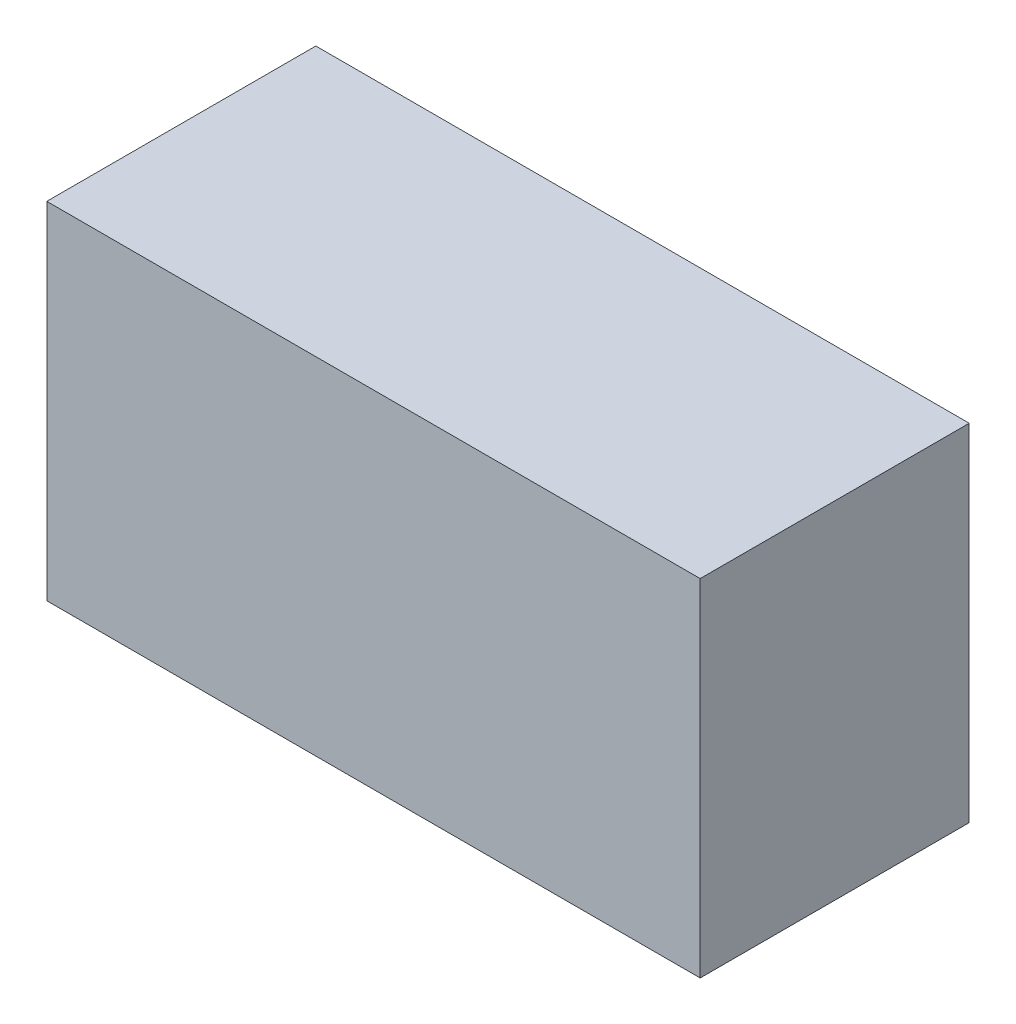
SolidWorks part; units mm, degrees
ref_plane "前视基准面" through (0, 0, 0) normal (0, 0, 1) x (1, 0, 0)
ref_plane "上视基准面" through (0, 0, 0) normal (0, 1, 0) x (1, 0, 0)
ref_plane "右视基准面" through (0, 0, 0) normal (1, 0, 0) x (0, 0, -1)
other "Configuration Table"
sketch "草图1" plane through (0, 0, 0) normal (0, 0, 1) x (1, 0, 0)
  line L1 (-42.5, -22.5) -> (42.5, -22.5)
  line L2 (-42.5, -22.5) -> (-42.5, 22.5)
  line L3 (-42.5, 22.5) -> (42.5, 22.5)
  line L4 (42.5, -22.5) -> (42.5, 22.5)
  line L5 (-42.5, -22.5) -> (42.5, 22.5) construction
  line L6 (-42.5, 22.5) -> (42.5, -22.5) construction
  point P0 (0, 0)
extrude "凸台-拉伸1" add sketch "草图1" along normal blind 35
